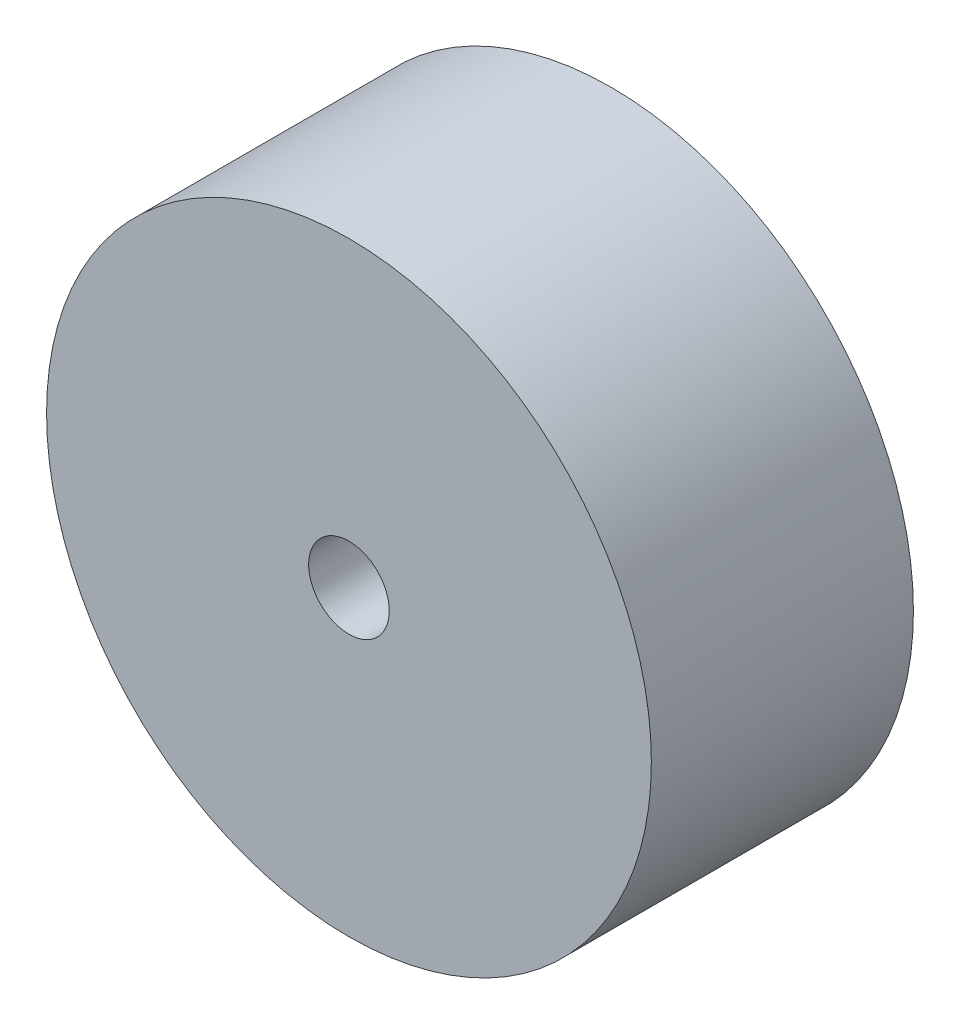
SolidWorks part; units mm, degrees
ref_plane "Front Plane" through (0, 0, 0) normal (0, 0, 1) x (1, 0, 0)
ref_plane "Top Plane" through (0, 0, 0) normal (0, 1, 0) x (1, 0, 0)
ref_plane "Right Plane" through (0, 0, 0) normal (1, 0, 0) x (0, 0, -1)
sketch "Sketch1" plane through (0, 0, 0) normal (0, 0, 1) x (1, 0, 0)
  circle A0 centre (0, 0) radius 30
  dimension "D1" = 60
extrude "Boss-Extrude1" add sketch "Sketch1" along normal blind 26
sketch "Sketch2" plane through (0, 0, 26) normal (0, 0, 1) x (1, 0, 0)
  circle A1 centre (0, 0) radius 4
  dimension "D2" = 8
extrude "Cut-Extrude1" cut sketch "Sketch2" against normal blind 10
